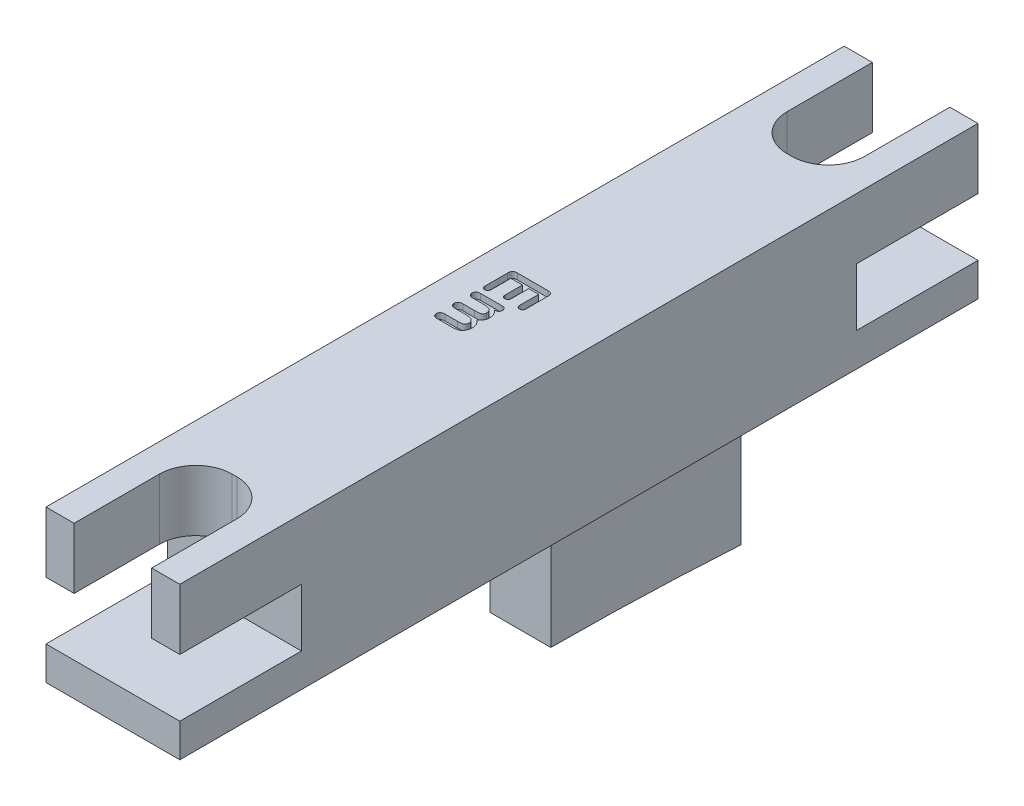
SolidWorks part; units mm, degrees
ref_plane "Front Plane" through (0, 0, 0) normal (0, 0, 1) x (1, 0, 0)
ref_plane "Top Plane" through (0, 0, 0) normal (0, 1, 0) x (1, 0, 0)
ref_plane "Right Plane" through (0, 0, 0) normal (1, 0, 0) x (0, 0, -1)
sketch "Sketch2" plane through (0, 0, 0) normal (0, 1, 0) x (1, 0, 0)
  line L1 (0, 0) -> (11.176, 0)
  line L2 (0, 0) -> (0, 66.675)
  line L3 (0, 66.675) -> (11.176, 66.675)
  line L4 (11.176, 0) -> (11.176, 66.675)
  dimension "D1" = 66.675
  dimension "D2" = 11.176
extrude "Boss-Extrude1" add sketch "Sketch2" along normal blind 12.7
sketch "Sketch3" plane through (0, 0, 0) normal (0, -1, 0) x (1, 0, 0)
  line L0 (11.176, -66.675) -> (0, -66.675) construction
  line L1 (2.794, 0) -> (7.874, 0)
  line L2 (2.794, 0) -> (2.794, -66.675)
  line L3 (2.794, -66.675) -> (7.874, -66.675)
  line L4 (7.874, 0) -> (7.874, -66.675)
  line L5 (0, -66.675) -> (0, 0) construction
  line L6 (0, 0) -> (11.176, 0) construction
  line L7 (-16.0623, -37.465) -> (21.3262, -37.465) construction
  line L8 (-9.1988, -29.21) -> (67.1361, -29.21) construction
  line L9 (2.794, -37.465) -> (2.794, -29.21) construction
  line L10 (-21.0326, -20.955) -> (28.4478, -20.955) construction
  line L11 (5.334, 0) -> (5.334, -66.675) construction
  line L12 (-27.1779, -45.72) -> (27.7068, -45.72) construction
  line L13 (2.794, -50.165) -> (7.874, -50.165)
  line L14 (7.874, -48.895) -> (2.794, -48.895)
  line L15 (7.874, -48.895) -> (7.874, -42.545) construction
  line L16 (7.874, -42.545) -> (2.794, -42.545)
  line L17 (2.794, -48.895) -> (2.794, -42.545) construction
  line L18 (7.874, -48.895) -> (2.794, -42.545) construction
  line L19 (7.874, -42.545) -> (2.794, -48.895) construction
  line L20 (7.874, -40.64) -> (2.794, -40.64)
  line L21 (7.874, -40.64) -> (7.874, -34.29)
  line L22 (7.874, -34.29) -> (2.794, -34.29)
  line L23 (2.794, -40.64) -> (2.794, -34.29)
  line L24 (7.874, -40.64) -> (2.794, -34.29) construction
  line L25 (7.874, -34.29) -> (2.794, -40.64) construction
  line L26 (7.874, -32.385) -> (2.794, -32.385)
  line L27 (7.874, -32.385) -> (7.874, -26.035)
  line L28 (7.874, -26.035) -> (2.794, -26.035)
  line L29 (2.794, -32.385) -> (2.794, -26.035)
  line L30 (7.874, -32.385) -> (2.794, -26.035) construction
  line L31 (7.874, -26.035) -> (2.794, -32.385) construction
  line L32 (7.874, -24.13) -> (2.794, -24.13)
  line L33 (7.874, -24.13) -> (7.874, -17.78)
  line L34 (7.874, -17.78) -> (2.794, -17.78)
  line L35 (2.794, -24.13) -> (2.794, -17.78)
  line L36 (7.874, -24.13) -> (2.794, -17.78) construction
  line L37 (7.874, -17.78) -> (2.794, -24.13) construction
  point P16 (2.794, -33.3375)
  point P17 (2.794, -33.3375)
  point P24 (5.334, -45.72)
  point P29 (5.334, -29.21)
  point P30 (5.334, -37.465)
  point P41 (5.334, -20.955)
  dimension "D1" = 5.08
  dimension "D2" = 2.794
  dimension "D3" = 8.255
  dimension "D4" = 8.255
  dimension "D5" = 8.255
  dimension "D6" = 5.08
  dimension "D7" = 6.35
  dimension "D8" = 6.35
  dimension "D9" = 6.35
  dimension "D10" = 6.35
  dimension "D11" = 1.27
extrude "Boss-Extrude2" add sketch "Sketch3" along normal blind 12.7 contours L4 L16 L2 L14 | L4 L20 L2 L16 | L4 L22 L2 L20 | L4 L14 L2 L13
sketch "Sketch4" plane through (0, 0, 0) normal (0, 0, 1) x (1, 0, 0)
  line L0 (0, 12.7) -> (11.176, 12.7) construction
  line L1 (0, 7.62) -> (2.3495, 7.62)
  line L2 (0, 7.62) -> (0, 2.794)
  line L3 (0, 2.794) -> (11.176, 2.794)
  line L4 (11.176, 7.62) -> (11.176, 2.794)
  line L5 (2.3495, 12.7) -> (8.8265, 12.7)
  line L6 (2.3495, 12.7) -> (2.3495, 7.62)
  line L8 (8.8265, 12.7) -> (8.8265, 7.62)
  line L9 (8.8265, 7.62) -> (11.176, 7.62)
  line L10 (11.176, 12.7) -> (11.176, 0) construction
  line L11 (0, 12.7) -> (0, 0) construction
  point P10 (5.588, 12.7)
  dimension "D2" = 6.477
  dimension "D3" = 4.826
  dimension "D4" = 5.08
extrude "Cut-Extrude1" cut sketch "Sketch4" against normal blind 10.16
ref_plane "Plane1" through (0, 0, -33.3375) normal (0, 0, 1) x (1, 0, 0)
fillet "Fillet2" radius 3.048 2 edges at (8.8265, 10.16, -10.16) (2.3495, 10.16, -10.16)
mirror "Mirror1" about plane through (0, 0, -33.3375) normal (0, 0, 1) of "Fillet2", "Cut-Extrude1"
sketch "Sketch5" plane through (2.794, 0, 0) normal (-1, 0, 0) x (0, 0, 1)
  line L0 (-33.3375, -10.668) -> (-33.3375, -12.7) construction
  line L2 (-66.675, -12.7) -> (0, -12.7)
  line L3 (-66.675, -12.7) -> (-66.675, 0) construction
  line L4 (-34.29, -12.7) -> (-50.165, -12.7) construction
  line L5 (0, 0) -> (0, -12.7) construction
  arc A0 (-66.675, -12.7) -> (0, -12.7) centre (-33.3375, -285.1557) cw
  dimension "D1" = 2.032
extrude "Cut-Extrude4" cut sketch "Sketch5" against normal through all
fillet "Fillet1" [suppressed] radius 2.54
sketch "Sketch6" plane through (0, 12.7, 0) normal (0, 1, 0) x (1, 0, 0)
  line L0 (2.3495, 7.112) -> (2.3495, 59.563) construction
  arc A0 (5.3975, 10.16) -> (2.3495, 7.112) centre (5.3975, 7.112) ccw construction
  text T0 "Em\r\n\r\n" font "Arial Rounded MT Bold" height 3.5
extrude "Cut-Extrude5" cut sketch "Sketch6" against normal blind 0.508
